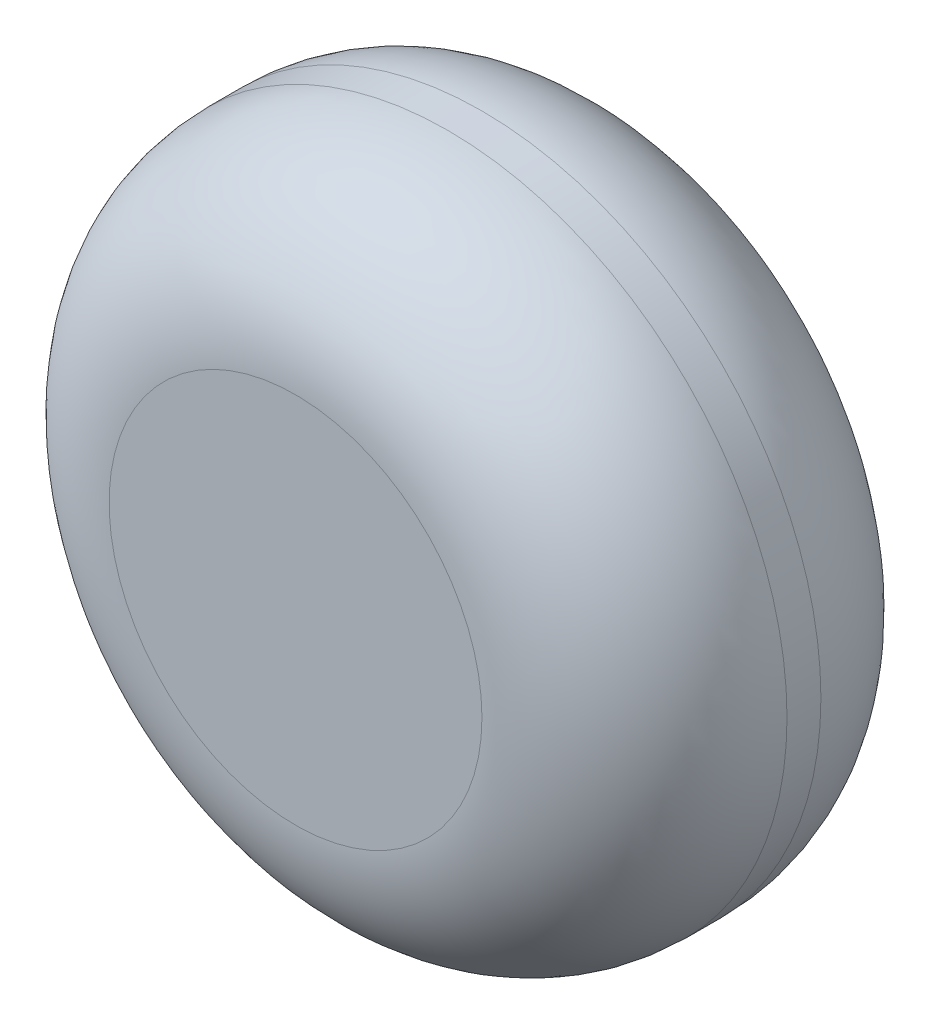
SolidWorks part; units mm, degrees
ref_plane "Front Plane" through (0, 0, 0) normal (0, 0, 1) x (1, 0, 0)
ref_plane "Top Plane" through (0, 0, 0) normal (0, 1, 0) x (1, 0, 0)
ref_plane "Right Plane" through (0, 0, 0) normal (1, 0, 0) x (0, 0, -1)
sketch "Sketch1" plane through (0, 0, 0) normal (0, 0, 1) x (1, 0, 0)
  circle A0 centre (0, 0) radius 100
  dimension "D1" = 200
extrude "Boss-Extrude1" add sketch "Sketch1" along normal mid plane 100
fillet "Fillet1" radius 45 2 edges at (100, 0, -50) (100, 0, 50)
